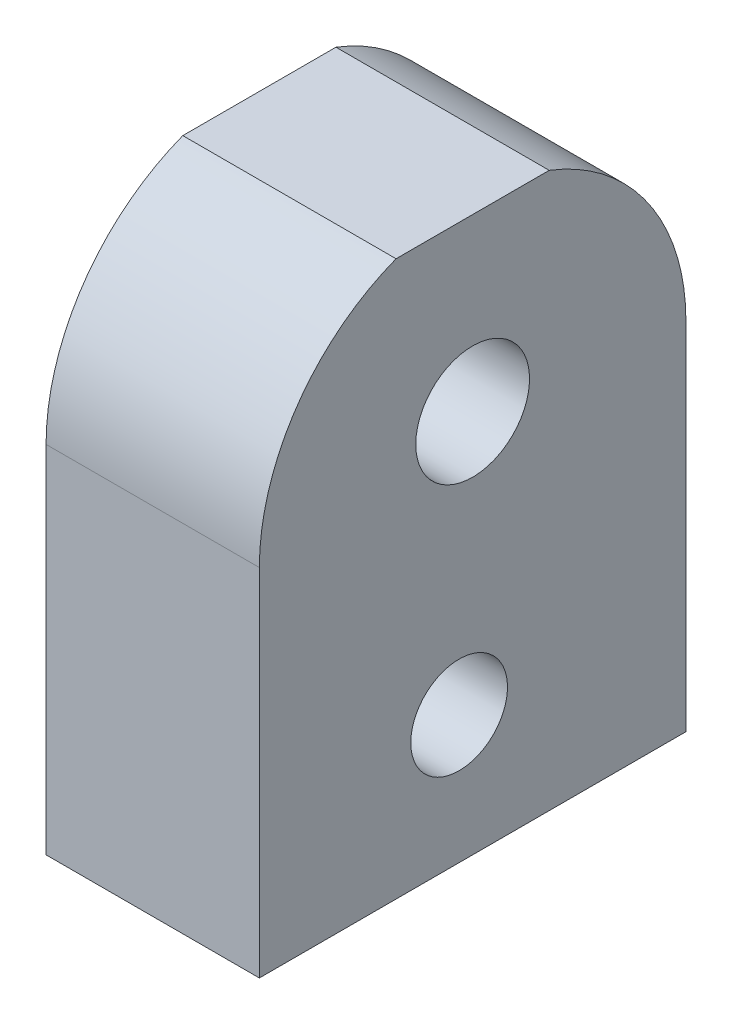
SolidWorks part; units mm, degrees
ref_plane "Front Plane" through (0, 0, 0) normal (0, 0, 1) x (1, 0, 0)
ref_plane "Top Plane" through (0, 0, 0) normal (0, 1, 0) x (1, 0, 0)
ref_plane "Right Plane" through (0, 0, 0) normal (1, 0, 0) x (0, 0, -1)
other "Configuration Table"
sketch "草图1" plane through (0, 0, 0) normal (0, 1, 0) x (1, 0, 0)
  line L0 (0, 0) -> (0, -30)
  line L1 (0, 0) -> (15, 0)
  line L2 (15, 0) -> (15, -30)
  line L3 (15, -30) -> (0, -30)
extrude "凸台-拉伸1" add sketch "草图1" along normal blind 25 contours L3 L0 L1 L2
sketch "草图3" plane through (0, 0, 0) normal (-1, 0, 0) x (0, 0, 1)
  line L0 (15, 25) -> (15, 0) construction
  line L1 (0, 25) -> (30, 25) construction
  line L2 (0, 0) -> (30, 0) construction
  line L7 (0, 25) -> (30, 25)
  circle A2 centre (15, 25) radius 15
  line M7 (30, 25) -> (0, 25)
  dimension "D1" = 0
extrude "凸台-拉伸3" add sketch "草图3" against normal blind 15 contours A2 L7 M7
sketch "草图4" plane through (0, 0, 0) normal (0, -1, 0) x (1, 0, 0)
  line L0 (7.5, 30) -> (7.5, 0) construction
  line L1 (15, 30) -> (0, 30) construction
  line L2 (0, 0) -> (15, 0) construction
  circle A1 centre (7.5, 24) radius 1.65
  circle A2 centre (7.5, 6) radius 1.65
  dimension "D1" = 6
  dimension "D2" = 6
extrude "切除-拉伸2" cut sketch "草图4" against normal blind 10 contours L0 A1 | A1 L0 | L0 A2 | A2 L0
sketch "草图5" plane through (0, 0, 0) normal (-1, 0, 0) x (0, 0, 1)
  line L0 (0, 0) -> (30, 0) construction
  line L2 (0, 25) -> (0, 0) construction
  circle A0 centre (15.95, 9) radius 3.4
  dimension "D2" = 6.8
  dimension "D1" = 9
  dimension "D3" = 15.95
sketch "草图9" plane through (0, 0, 0) normal (-1, 0, 0) x (0, 0, 1)
  line L0 (15, 27) -> (15, 40) construction
  circle A0 centre (15, 27) radius 6.1
  arc A1 (30, 25) -> (0, 25) centre (15, 25) ccw construction
  dimension "D1" = 12.2
extrude "切除-拉伸3" cut sketch "草图9" against normal blind 6
sketch "草图10" plane through (6, 0, 0) normal (-1, 0, 0) x (0, 0, 1)
  circle A0 centre (15, 27) radius 4
  dimension "D1" = 8
extrude "切除-拉伸4" cut sketch "草图10" against normal through all contours A0
sketch "草图12" plane through (0, 0, 0) normal (-1, 0, 0) x (0, 0, 1)
  line L0 (15, 39) -> (15, 25) construction
  line L1 (9.6148, 39) -> (20.3852, 39)
  arc A1 (30, 25) -> (0, 25) centre (15, 25) ccw construction
  point P9 (15, 39)
  arc M7 (30, 25) -> (0, 25) centre (15, 25) ccw
extrude "切除-拉伸6" cut sketch "草图12" against normal through all and the other way through all contours L1 M7
extrude "切除-拉伸7" cut sketch "草图5" against normal through all
